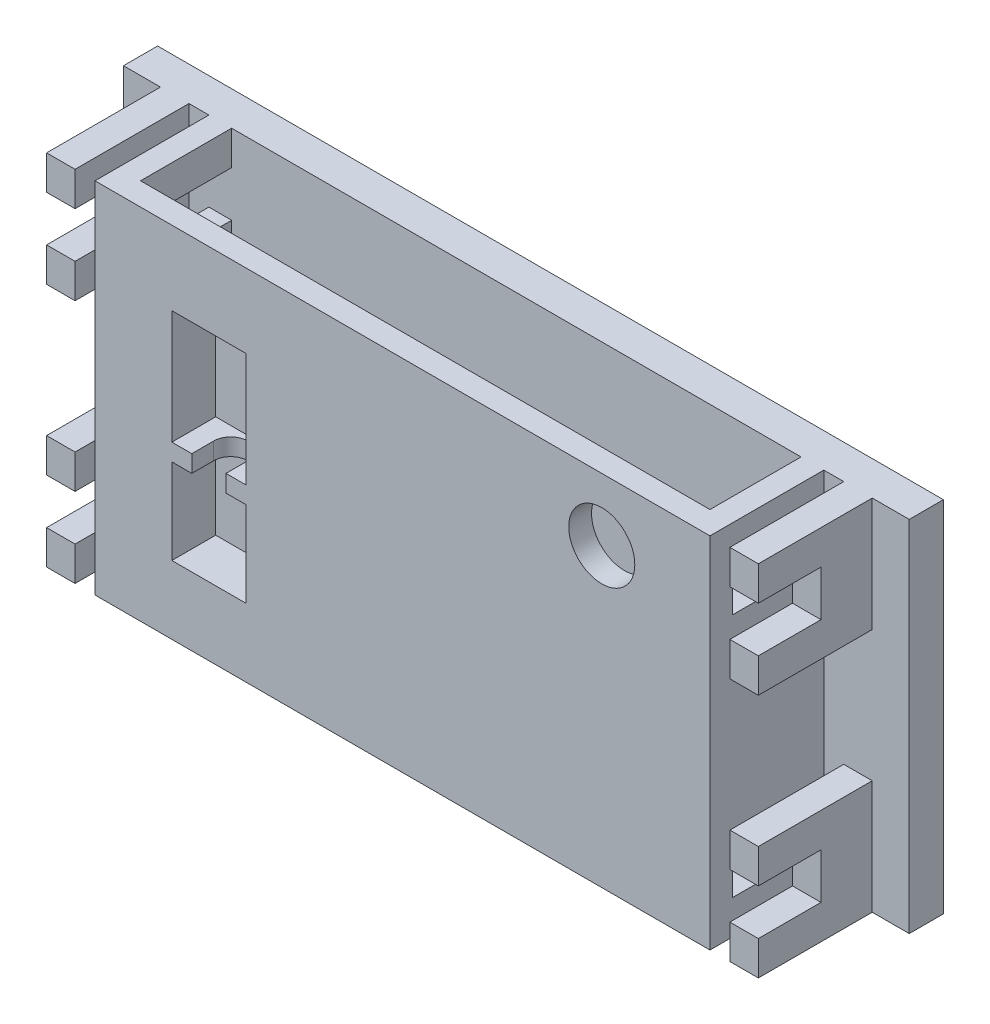
SolidWorks part; units mm, degrees
ref_plane "Plano frontal" through (0, 0, 0) normal (0, 0, 1) x (1, 0, 0)
ref_plane "Plano superior" through (0, 0, 0) normal (0, 1, 0) x (1, 0, 0)
ref_plane "Plano direito" through (0, 0, 0) normal (1, 0, 0) x (0, 0, -1)
sketch "Esboço1" plane through (0, 0, 0) normal (0, 0, 1) x (1, 0, 0)
  line L0 (0, -31.682) -> (0, -0.182)
  line L1 (0, -31.682) -> (-69, -31.682)
  line L3 (0, -0.182) -> (-69, -0.182)
  line L4 (-69, -31.682) -> (-69, -0.182)
  point P0 (0, 0)
  dimension "D1" = 31.5
  dimension "D2" = 69
extrude "Ressalto-extrusão1" add sketch "Esboço1" along normal blind 6
sketch "Esboço2" plane through (0, 0, 6) normal (0, 0, 1) x (1, 0, 0)
  line L0 (-69, -31.682) -> (0, -31.682) construction
  line L1 (-62.5, -31.682) -> (-57.5, -31.682)
  line L2 (-62.5, -31.682) -> (-62.5, -11.682)
  line L3 (-62.5, -11.682) -> (-57.5, -11.682)
  line L4 (-57.5, -31.682) -> (-57.5, -11.682)
  line L5 (-69, -0.182) -> (-69, -31.682) construction
  dimension "D1" = 20
  dimension "D2" = 5
  dimension "D3" = 6.5
extrude "Ressalto-extrusão2" add sketch "Esboço2" along normal blind 20
sketch "Esboço3" plane through (0, 0, 26) normal (0, 0, 1) x (1, 0, 0)
  line L0 (-57.5, -31.682) -> (-57.5, -11.682) construction
  line L1 (-57.5, -17.682) -> (-62.5, -17.682)
  line L2 (-57.5, -17.682) -> (-57.5, -25.682)
  line L3 (-57.5, -25.682) -> (-62.5, -25.682)
  line L4 (-62.5, -17.682) -> (-62.5, -25.682)
  line L5 (-62.5, -11.682) -> (-62.5, -31.682) construction
  line L6 (-57.5, -11.682) -> (-62.5, -11.682) construction
  line L7 (-62.5, -31.682) -> (-57.5, -31.682) construction
  dimension "D1" = 6
  dimension "D2" = 6
extrude "Corte-extrusão1" cut sketch "Esboço3" against normal blind 11
sketch "Esboço4" plane through (0, 0, 6) normal (0, 0, 1) x (1, 0, 0)
  line L0 (-57.5, -31.682) -> (0, -31.682) construction
  line L1 (-54, -31.682) -> (-50, -31.682)
  line L2 (-54, -31.682) -> (-54, -0.182)
  line L3 (-54, -0.182) -> (-50, -0.182)
  line L4 (-50, -31.682) -> (-50, -0.182)
  line L5 (0, -0.182) -> (-69, -0.182) construction
  line L6 (-57.5, -31.682) -> (-57.5, -11.682) construction
  dimension "D1" = 3.5
  dimension "D2" = 4
extrude "Ressalto-extrusão3" add sketch "Esboço4" along normal blind 20
sketch "Esboço5" plane through (-50, 0, 0) normal (1, 0, 0) x (0, 0, -1)
  line L0 (-15, -25.682) -> (-6, -25.682)
  line L2 (-22, -17.682) -> (-22, -6.182)
  line L5 (-15, -17.682) -> (-6, -17.682)
  line L6 (-22, -6.182) -> (-22, -0.182)
  line L7 (-26, -0.182) -> (-6, -0.182) construction
  line L10 (-26, -31.682) -> (-26, -0.182) construction
  line L11 (-22, -17.682) -> (-22, -25.682)
  line L12 (-6, -31.682) -> (-6, -0.182) construction
  line L13 (-6, -25.682) -> (-6, -17.682)
  line L20 (-15, -17.682) -> (-15, -25.682)
  line L21 (-15, -25.682) -> (-26, -25.682)
  line L22 (-26, -25.682) -> (-26, -31.682)
  line L23 (-26, -31.682) -> (-6, -31.682)
  line L24 (-6, -31.682) -> (-6, -11.682)
  line L25 (-6, -11.682) -> (-26, -11.682)
  line L26 (-26, -11.682) -> (-26, -17.682)
  line L27 (-26, -17.682) -> (-15, -17.682)
  line L29 (-15, -25.682) -> (-22, -25.682)
  line L32 (-6, -25.682) -> (-6, -17.682)
  line L35 (-22, -17.682) -> (-15, -17.682)
  line M8 (-6, -31.682) -> (-6, -0.182)
  dimension "D1" = 4
  dimension "D2" = 0
extrude "Corte-extrusão2" cut sketch "Esboço5" against normal up to surface (4 mm away) contours L35 L11 L29 L0 L5 M8
sketch "Esboço6" plane through (-50, 0, 0) normal (1, 0, 0) x (0, 0, -1)
  line L0 (-26, -31.682) -> (-26, -0.182) construction
  line L1 (-26, -31.682) -> (-22, -31.682)
  line L2 (-26, -31.682) -> (-26, -0.182)
  line L5 (-22, -31.682) -> (-22, -0.182)
  line L6 (-26, -0.182) -> (-6, -0.182) construction
  line L7 (-22, -0.182) -> (-26, -0.182)
  line L8 (-22, -17.682) -> (-22, -25.682) construction
extrude "Ressalto-extrusão4" add sketch "Esboço6" along normal up to surface (50 mm away) up to face at (0, -15.932, 3)
ref_plane "Plano2" through (0, -0.182, 0) normal (0, 1, 0) x (1, 0, 0)
mirror "Espelhar10" about plane through (0, -0.182, 0) normal (0, 1, 0) of bodies 110 103
ref_plane "Plano1" through (0, 0, 0) normal (1, 0, 0) x (0, 0, -1)
mirror "Espelhar11" about plane through (0, 0, 0) normal (1, 0, 0) of bodies 106
sketch "Esboço18" plane through (-54, 0, 0) normal (-1, 0, 0) x (0, 0, 1)
  line L0 (6, -31.682) -> (26, 31.318) construction
  line L1 (6, 31.318) -> (26, -31.682) construction
  line L12 (6, -17.682) -> (22, -17.682)
  line L13 (22, -17.682) -> (22, -25.682)
  line L14 (22, -25.682) -> (6, -25.682)
  line L15 (6, -25.682) -> (6, -31.682)
  line L16 (6, -31.682) -> (26, -31.682)
  line L17 (26, -31.682) -> (26, 31.318)
  line L18 (26, 31.318) -> (6, 31.318)
  line L19 (6, 31.318) -> (6, 25.318)
  line L20 (6, 25.318) -> (22, 25.318)
  line L21 (22, 25.318) -> (22, 17.318)
  line L22 (22, 17.318) -> (6, 17.318)
  line L23 (6, 17.318) -> (6, -17.682)
  line L24 (6, -17.682) -> (22, -17.682)
  line L25 (22, -17.682) -> (22, -25.682)
  line L26 (22, -25.682) -> (6, -25.682)
  line L27 (6, -25.682) -> (6, -31.682)
  line L28 (6, -31.682) -> (26, -31.682)
  line L29 (26, -31.682) -> (26, 31.318)
  line L30 (26, 31.318) -> (6, 31.318)
  line L31 (6, 31.318) -> (6, 25.318)
  line L32 (6, 25.318) -> (22, 25.318)
  line L33 (22, 25.318) -> (22, 17.318)
  line L34 (22, 17.318) -> (6, 17.318)
  line L35 (6, 17.318) -> (6, -17.682)
  circle A0 centre (16, -0.182) radius 3.8
  dimension "D2" = 7.6
  dimension "D1" = 0
extrude "Corte-extrusão3" cut sketch "Esboço18" against normal up to surface (4 mm away) contours A0 up to face at (-50, -0.182, 14)
sketch "Esboço19" plane through (0, 0, 26) normal (0, 0, 1) x (1, 0, 0)
  line L0 (20, -31.682) -> (50, -31.682)
  line L7 (50, -31.682) -> (20, -31.682)
  line L8 (50, -31.682) -> (50, 31.318)
  line L9 (50, 31.318) -> (20, 31.318)
  line L10 (20, -31.682) -> (20, 31.318)
  line L11 (35, -31.682) -> (35, 31.318) construction
  line L13 (20, 20.318) -> (50, 20.318) construction
  line L20 (-54, -17.682) -> (-54, -25.682)
  line L21 (-50, -17.682) -> (-54, -17.682)
  line L22 (-50, 17.318) -> (-50, -17.682)
  line L23 (-54, 17.318) -> (-50, 17.318)
  line L24 (-54, 25.318) -> (-54, 17.318)
  line L25 (-50, 25.318) -> (-54, 25.318)
  line L26 (-50, 31.318) -> (-50, 25.318)
  line L27 (50, 31.318) -> (-50, 31.318)
  line L28 (50, 25.318) -> (50, 31.318)
  line L29 (54, 25.318) -> (50, 25.318)
  line L30 (54, 17.318) -> (54, 25.318)
  line L31 (50, 17.318) -> (54, 17.318)
  line L32 (50, -17.682) -> (50, 17.318)
  line L33 (54, -17.682) -> (50, -17.682)
  line L34 (54, -25.682) -> (54, -17.682)
  line L35 (50, -25.682) -> (54, -25.682)
  line L36 (50, -31.682) -> (50, -25.682)
  line L37 (-50, -31.682) -> (50, -31.682)
  line L38 (-50, -25.682) -> (-50, -31.682)
  line L39 (-54, -25.682) -> (-50, -25.682)
  line L47 (50, 31.318) -> (-50, 31.318)
  line L48 (50, 25.318) -> (50, 31.318)
  line L49 (54, 25.318) -> (50, 25.318)
  line L50 (54, 17.318) -> (54, 25.318)
  line L51 (50, 17.318) -> (54, 17.318)
  line L52 (50, -17.682) -> (50, 17.318)
  line L53 (54, -17.682) -> (50, -17.682)
  line L54 (54, -25.682) -> (54, -17.682)
  line L55 (50, -25.682) -> (54, -25.682)
  line L56 (50, -31.682) -> (50, -25.682)
  line L57 (-50, -31.682) -> (50, -31.682)
  circle A1 centre (35, 20.318) radius 5.8
  dimension "D7" = 11.6
  dimension "D5" = 30
  dimension "D6" = 11
  dimension "D1" = 0
extrude "Corte-extrusão5" cut sketch "Esboço19" against normal up to surface (4 mm away) contours A1 up to face at (0, -0.182, 22)
sketch "Esboço20" plane through (0, 0, 22) normal (0, 0, -1) x (-1, 0, 0)
  line L0 (34, 22.318) -> (34, 31.318) construction
  line L5 (24, 22.318) -> (44, 22.318)
  line L6 (24, 22.318) -> (24, -22.682)
  line L7 (24, -22.682) -> (44, -22.682)
  line L8 (44, 22.318) -> (44, -22.682)
  line L10 (34, -22.682) -> (34, -31.682) construction
  line L20 (54, -25.682) -> (54, -17.682)
  line L21 (54, -17.682) -> (50, -17.682)
  line L22 (50, -17.682) -> (50, 17.318)
  line L23 (50, 17.318) -> (54, 17.318)
  line L24 (54, 17.318) -> (54, 25.318)
  line L25 (54, 25.318) -> (50, 25.318)
  line L26 (50, 25.318) -> (50, 31.318)
  line L27 (50, 31.318) -> (-50, 31.318)
  line L28 (-50, 31.318) -> (-50, 25.318)
  line L29 (-50, 25.318) -> (-54, 25.318)
  line L30 (-54, 25.318) -> (-54, 17.318)
  line L31 (-54, 17.318) -> (-50, 17.318)
  line L32 (-50, 17.318) -> (-50, -17.682)
  line L33 (-50, -17.682) -> (-54, -17.682)
  line L34 (-54, -17.682) -> (-54, -25.682)
  line L35 (-54, -25.682) -> (-50, -25.682)
  line L36 (-50, -25.682) -> (-50, -31.682)
  line L37 (-50, -31.682) -> (50, -31.682)
  line L38 (50, -31.682) -> (50, -25.682)
  line L39 (50, -25.682) -> (54, -25.682)
  line L40 (54, -25.682) -> (54, -17.682)
  line L41 (54, -17.682) -> (50, -17.682)
  line L42 (50, -17.682) -> (50, 17.318)
  line L43 (50, 17.318) -> (54, 17.318)
  line L44 (54, 17.318) -> (54, 25.318)
  line L45 (54, 25.318) -> (50, 25.318)
  line L46 (50, 25.318) -> (50, 31.318)
  line L47 (50, 31.318) -> (-50, 31.318)
  line L48 (-50, 31.318) -> (-50, 25.318)
  line L49 (-50, 25.318) -> (-54, 25.318)
  line L50 (-54, 25.318) -> (-54, 17.318)
  line L51 (-54, 17.318) -> (-50, 17.318)
  line L52 (-50, 17.318) -> (-50, -17.682)
  line L53 (-50, -17.682) -> (-54, -17.682)
  line L54 (-54, -17.682) -> (-54, -25.682)
  line L55 (-54, -25.682) -> (-50, -25.682)
  line L56 (-50, -25.682) -> (-50, -31.682)
  line L57 (-50, -31.682) -> (50, -31.682)
  line L58 (50, -31.682) -> (50, -25.682)
  line L59 (50, -25.682) -> (54, -25.682)
  dimension "D2" = 45
  dimension "D3" = 20
  dimension "D4" = 6
  dimension "D1" = 0
extrude "Ressalto-extrusão9" add sketch "Esboço20" along normal blind 7 contours L8 L5 L6 L7
sketch "Esboço21" plane through (0, 0, 26) normal (0, 0, 1) x (1, 0, 0)
  line L0 (-40.5, -12.182) -> (-44, -12.182) construction
  line L1 (-40.5, -19.682) -> (-27.5, -19.682)
  line L2 (-40.5, -19.682) -> (-40.5, -4.682)
  line L3 (-40.5, -4.682) -> (-27.5, -4.682)
  line L4 (-44, 22.318) -> (-44, -22.682)
  line L5 (-24, 22.318) -> (-44, 22.318)
  line L6 (-24, -22.682) -> (-24, 22.318)
  line L7 (-44, -22.682) -> (-24, -22.682)
  line L8 (-44, 22.318) -> (-44, -22.682)
  line L9 (-24, 22.318) -> (-44, 22.318)
  line L10 (-24, -22.682) -> (-24, 22.318)
  line L11 (-44, -22.682) -> (-24, -22.682)
  line L12 (-27.5, -19.682) -> (-27.5, -4.682)
  line L13 (-24, -12.182) -> (-27.5, -12.182) construction
  dimension "D2" = 13
  dimension "D3" = 15
  dimension "D4" = 3
  dimension "D1" = 0
extrude "Corte-extrusão6" cut sketch "Esboço21" against normal blind 7.7 contours L2 L1 L12 L3
sketch "Esboço22" plane through (0, 0, 26) normal (0, 0, 1) x (1, 0, 0)
  line L0 (-40.5, -19.682) -> (-40.5, -4.682) construction
  line L1 (-40.5, -1.682) -> (-27.5, -1.682)
  line L2 (-40.5, -1.682) -> (-40.5, 18.318)
  line L3 (-40.5, 18.318) -> (-27.5, 18.318)
  line L4 (-44, 22.318) -> (-44, -22.682)
  line L5 (-24, 22.318) -> (-44, 22.318)
  line L6 (-24, -22.682) -> (-24, 22.318)
  line L7 (-44, -22.682) -> (-24, -22.682)
  line L8 (-44, 22.318) -> (-44, -22.682)
  line L9 (-24, 22.318) -> (-44, 22.318)
  line L10 (-24, -22.682) -> (-24, 22.318)
  line L11 (-44, -22.682) -> (-24, -22.682)
  line L12 (-27.5, -1.682) -> (-27.5, 18.318)
  line L17 (-27.5, -4.682) -> (-40.5, -4.682)
  line L18 (-40.5, -4.682) -> (-40.5, -19.682)
  line L19 (-40.5, -19.682) -> (-27.5, -19.682)
  line L20 (-27.5, -19.682) -> (-27.5, -4.682)
  line L21 (-27.5, -4.682) -> (-40.5, -4.682)
  line L22 (-40.5, -4.682) -> (-40.5, -19.682)
  line L23 (-40.5, -19.682) -> (-27.5, -19.682)
  line L24 (-27.5, -19.682) -> (-27.5, -4.682)
  dimension "D2" = 20
  dimension "D3" = 13
  dimension "D5" = 3
  dimension "D1" = 0
  dimension "D4" = 0
extrude "Corte-extrusão7" cut sketch "Esboço22" against normal blind 7.7 contours L2 L1 L12 L3
sketch "Esboço23" plane through (0, -1.682, 0) normal (0, 1, 0) x (1, 0, 0)
  line L0 (-27.5, -26) -> (-40.5, -18.3) construction
  line L1 (-40.5, -26) -> (-27.5, -18.3) construction
  line L2 (-31, -22.15) -> (-27.5, -22.15)
  line L3 (-37, -22.15) -> (-40.5, -22.15)
  line L4 (-40.5, -26) -> (-27.5, -26)
  line L5 (-27.5, -26) -> (-27.5, -18.3)
  line L6 (-27.5, -18.3) -> (-40.5, -18.3)
  line L7 (-40.5, -18.3) -> (-40.5, -26)
  line L8 (-40.5, -26) -> (-27.5, -26)
  line L9 (-27.5, -26) -> (-27.5, -18.3)
  line L10 (-27.5, -18.3) -> (-40.5, -18.3)
  line L11 (-40.5, -18.3) -> (-40.5, -26)
  line L12 (-31, -22.15) -> (-31, -26)
  line L13 (-37, -22.15) -> (-37, -26)
  arc A0 (-31, -22.15) -> (-37, -22.15) centre (-34, -22.15) ccw
  dimension "D2" = 6
  dimension "D1" = 0
extrude "Corte-extrusão9" cut sketch "Esboço23" against normal up to surface (3 mm away) contours L12 A0 L13 L8 up to face at (-34, -4.682, 22.15)
